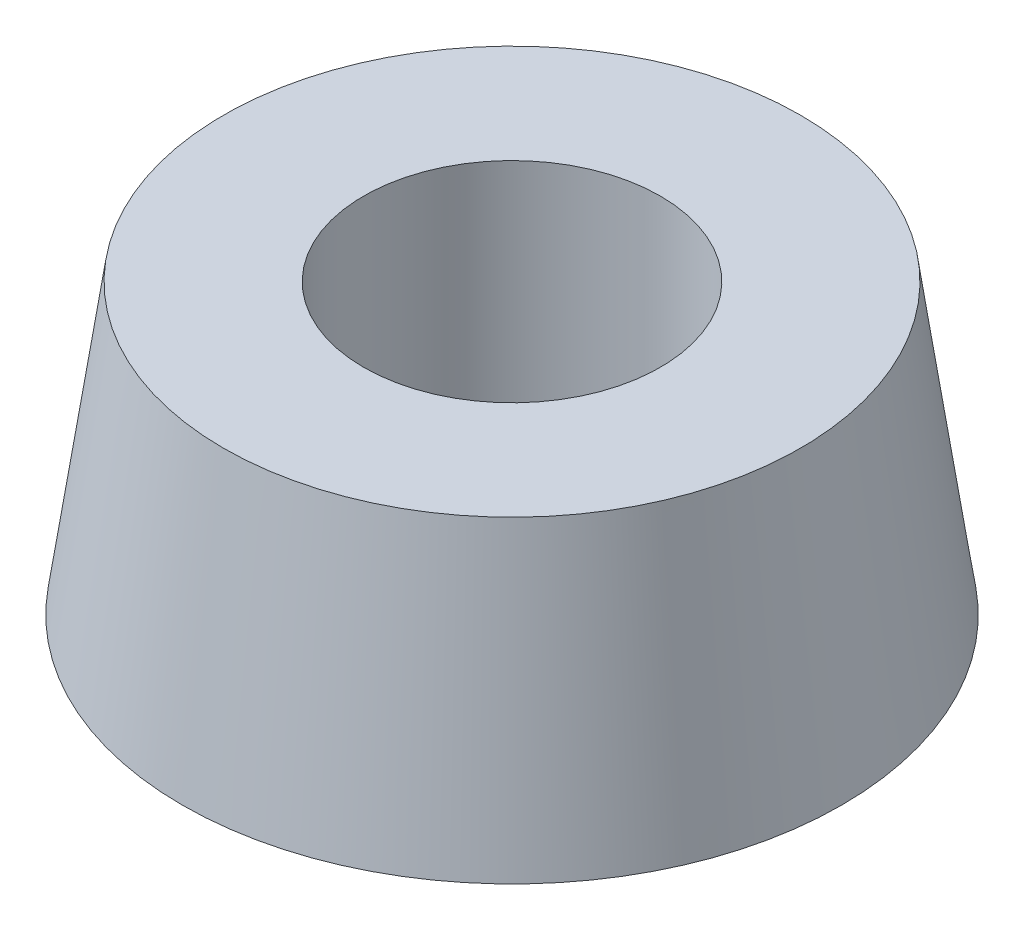
SolidWorks part; units mm, degrees
ref_plane "前视基准面" through (0, 0, 0) normal (0, 0, 1) x (1, 0, 0)
ref_plane "上视基准面" through (0, 0, 0) normal (0, 1, 0) x (1, 0, 0)
ref_plane "右视基准面" through (0, 0, 0) normal (1, 0, 0) x (0, 0, -1)
sketch "草图1" plane through (0, 0, 0) normal (0, 1, 0) x (1, 0, 0)
  circle A0 centre (0, 0) radius 12
  dimension "D1" = 24
ref_plane "基准面1" through (0, 10.5, 0) normal (0, 1, 0) x (1, 0, 0)
sketch "草图2" plane through (0, 10.5, 0) normal (0, 1, 0) x (1, 0, 0)
  circle A0 centre (0, 0) radius 10.5
  dimension "D1" = 21
loft "放样1" add profiles "草图1", "草图2"
sketch "草图4" plane through (0, 10.5, 0) normal (0, 1, 0) x (1, 0, 0)
  circle A0 centre (0, 0) radius 5.4
  dimension "D1" = 10.8
extrude "切除-拉伸1" cut sketch "草图4" against normal through all
